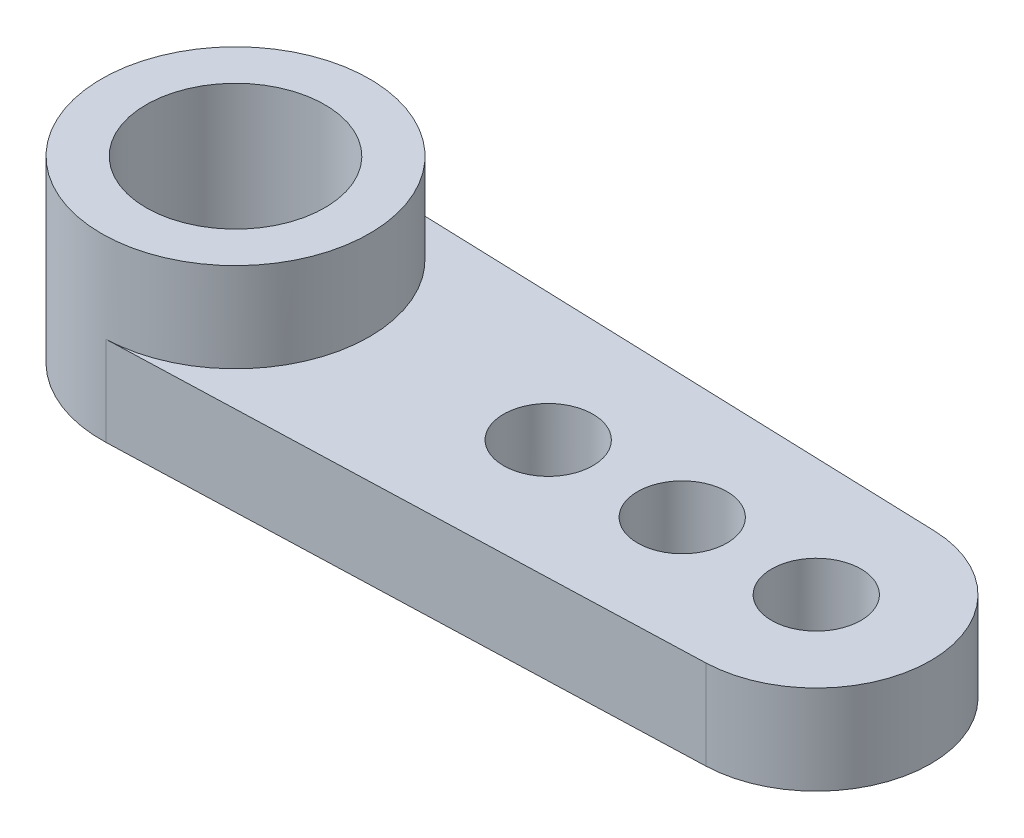
SolidWorks part; units mm, degrees
ref_plane "Plan de face" through (0, 0, 0) normal (0, 0, 1) x (1, 0, 0)
ref_plane "Plan de dessus" through (0, 0, 0) normal (0, 1, 0) x (1, 0, 0)
ref_plane "Plan de droite" through (0, 0, 0) normal (1, 0, 0) x (0, 0, -1)
sketch "Esquisse1" plane through (0, 0, 0) normal (0, 1, 0) x (1, 0, 0)
  line L0 (-41.285, 3) -> (-28.2999, 2.5602)
  line L1 (-41.285, -2.9966) -> (-28.2999, -2.5568)
  arc A0 (-28.2999, 2.5602) -> (-28.2999, -2.5568) centre (-28.3865, 0.0017) cw
  arc A1 (-41.285, 3) -> (-41.285, -2.9966) centre (-41.3865, 0.0017) ccw
  dimension "D1" = 13
extrude "Extrusion1" add sketch "Esquisse1" along normal blind 2
sketch "Esquisse2" plane through (0, 2, 0) normal (0, 1, 0) x (-1, 0, 0)
  circle A0 centre (34.3865, -0.0017) radius 1
  circle A1 centre (31.3865, -0.0017) radius 1
  circle A2 centre (28.3865, -0.0017) radius 1
  dimension "D3" = 2
  dimension "D4" = 2
  dimension "D1" = 3
  dimension "D2" = 3
extrude "Extrusion2" cut sketch "Esquisse2" against normal up to next
sketch "Esquisse3" plane through (0, 2, 0) normal (0, 1, 0) x (1, 0, 0)
  circle A0 centre (-41.3865, 0.0017) radius 3
  circle A1 centre (-41.3865, 0.0017) radius 2
  dimension "D1" = 6
  dimension "D2" = 4
extrude "Extrusion3" add sketch "Esquisse3" along normal blind 2
sketch "Esquisse4" plane through (0, 2, 0) normal (0, 1, 0) x (1, 0, 0)
  circle A0 centre (-41.3865, 0.0017) radius 2
extrude "Extrusion4" cut sketch "Esquisse4" against normal blind 1
